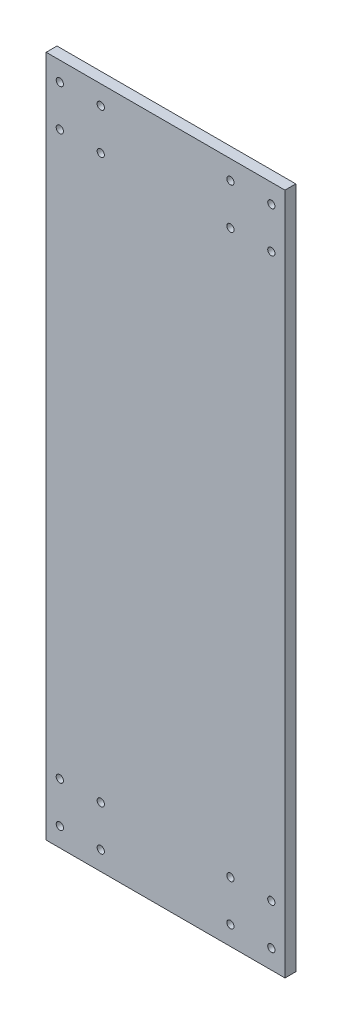
SolidWorks part; units mm, degrees
ref_plane "Front Plane" through (0, 0, 0) normal (0, 0, 1) x (1, 0, 0)
ref_plane "Top Plane" through (0, 0, 0) normal (0, 1, 0) x (1, 0, 0)
ref_plane "Right Plane" through (0, 0, 0) normal (1, 0, 0) x (0, 0, -1)
sketch "Sketch1" plane through (0, 0, 0) normal (0, 0, 1) x (1, 0, 0)
  line L0 (0, 200) -> (0, -200) construction
  line L1 (-70, -200) -> (70, -200)
  line L2 (-70, -200) -> (-70, 200)
  line L3 (-70, 200) -> (70, 200)
  line L4 (70, -200) -> (70, 200)
  line L5 (-70, -200) -> (70, 200) construction
  line L6 (-70, 200) -> (70, -200) construction
  line L7 (-70, 0) -> (70, 0) construction
  line L8 (-70, 196.825) -> (0, 196.825) construction
  line L9 (-50, 192.1136) -> (-50, 168.9658) construction
  line L12 (-63.1537, 176.825) -> (-35.7543, 176.825) construction
  circle A9 centre (-62, 188.825) radius 2.125
  circle A11 centre (-38, 188.825) radius 2.125
  circle A12 centre (-38, 164.825) radius 2.125
  circle A13 centre (-62, 164.825) radius 2.125
  circle A14 centre (38, 164.825) radius 2.125
  circle A15 centre (62, 164.825) radius 2.125
  circle A16 centre (38, 188.825) radius 2.125
  circle A17 centre (62, 188.825) radius 2.125
  circle A18 centre (62, -188.825) radius 2.125
  circle A19 centre (38, -188.825) radius 2.125
  circle A20 centre (62, -164.825) radius 2.125
  circle A21 centre (38, -164.825) radius 2.125
  circle A22 centre (-62, -164.825) radius 2.125
  circle A23 centre (-38, -164.825) radius 2.125
  circle A24 centre (-38, -188.825) radius 2.125
  circle A25 centre (-62, -188.825) radius 2.125
  point P0 (0, 0)
  dimension "D4" = 4.25
  dimension "D6" = 8
  dimension "D7" = 12
  dimension "D1" = 400
  dimension "D2" = 140
  dimension "D3" = 3.175
  dimension "D5" = 8
  dimension "D8" = 12
extrude "Boss-Extrude1" add sketch "Sketch1" along normal blind 6.35
